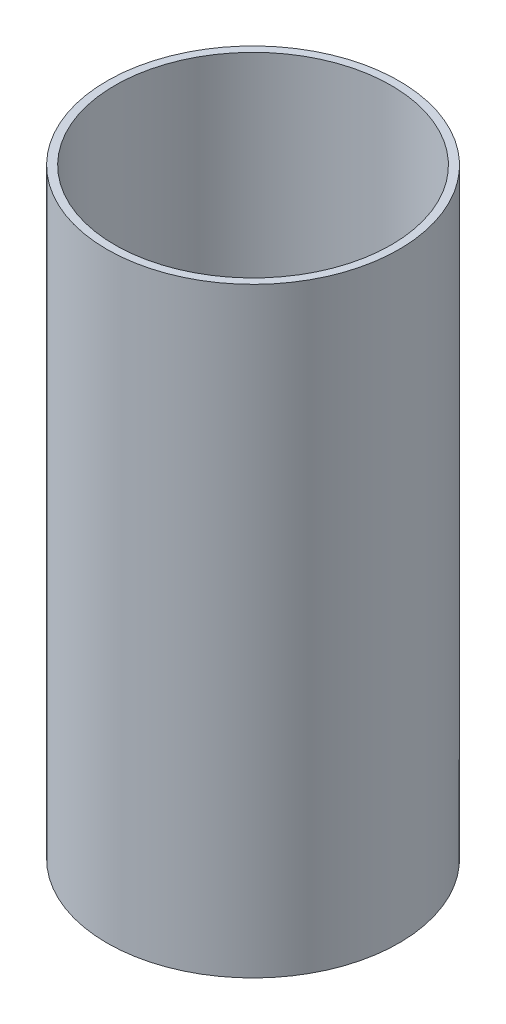
SolidWorks part; units mm, degrees
material "Thornel Mat VMA"
ref_plane "Alzado" through (0, 0, 0) normal (0, 0, 1) x (1, 0, 0)
ref_plane "Planta" through (0, 0, 0) normal (0, 1, 0) x (1, 0, 0)
ref_plane "Vista lateral" through (0, 0, 0) normal (1, 0, 0) x (0, 0, -1)
sketch "Croquis1" plane through (0, 0, 0) normal (0, 1, 0) x (1, 0, 0)
  circle A0 centre (0, 0) radius 70
  dimension "D1" = 140
extrude "Extruir-Lámina1" add sketch "Croquis1" along normal blind 288 thin thin type one direction reverse wall 3.75
